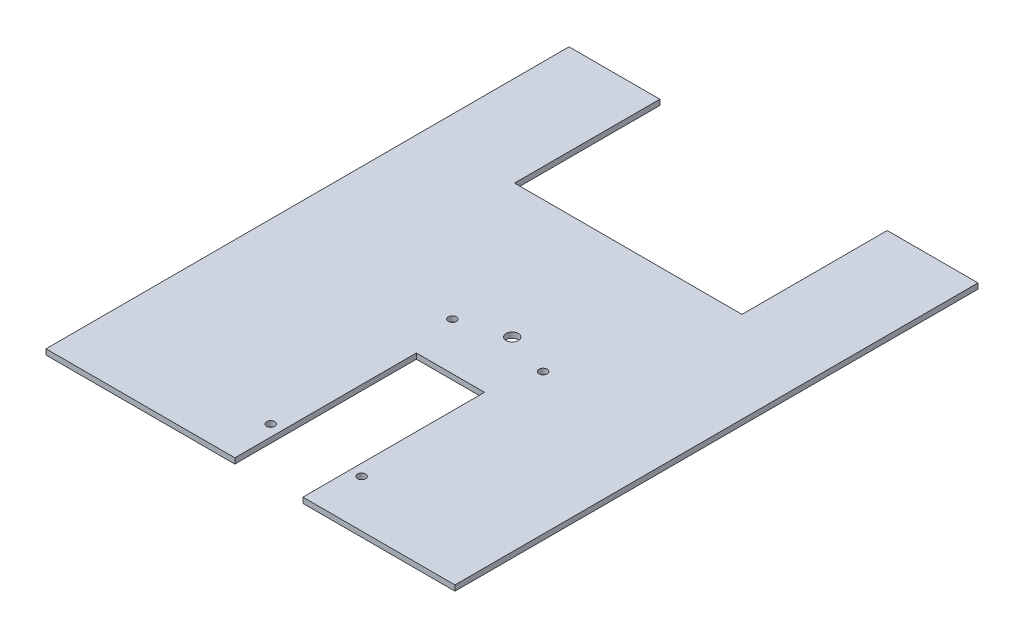
SolidWorks part; units mm, degrees
ref_plane "Front Plane" through (0, 0, 0) normal (0, 0, 1) x (1, 0, 0)
ref_plane "Top Plane" through (0, 0, 0) normal (0, 1, 0) x (1, 0, 0)
ref_plane "Right Plane" through (0, 0, 0) normal (1, 0, 0) x (0, 0, -1)
sketch "Sketch1" plane through (0, 0, 0) normal (0, 1, 0) x (1, 0, 0)
  line L0 (0, 144.035) -> (0, -144.035) construction
  line L1 (-112.62, -144.035) -> (112.62, -144.035)
  line L2 (-112.62, -144.035) -> (-112.62, 144.035)
  line L3 (-112.62, 144.035) -> (112.62, 144.035)
  line L4 (112.62, -144.035) -> (112.62, 144.035)
  dimension "D1" = 288.07
  dimension "D2" = 225.24
extrude "Boss-Extrude1" add sketch "Sketch1" along normal mid plane 3
hole_wizard "M4 Clearance Hole1" positions "Sketch2" profile "Sketch3" hole size "M4" standard "ANSI Metric" end condition up to next
sketch "Sketch2" plane through (0, 1.5, 0) normal (0, 1, 0) x (1, 0, 0)
  point P0 (-14.88, -117.99)
  point P2 (-14.88, -17.99)
  point P4 (35.13, -117.99)
  point P6 (35.13, -17.99)
  point P17 (-14.88, -117.99)
  point P19 (-14.88, -17.99)
  point P21 (35.13, -17.99)
  point P23 (35.13, -117.99)
sketch "Sketch3" plane through (-14.88, 1.5, 117.99) normal (1, 0, 0) x (0, 0, 1)
  line L0 (0, 0) -> (0, 3)
  line L1 (0, 3) -> (2.25, 3)
  line L2 (2.25, 3) -> (2.25, 0)
  line L5 (2.25, 0) -> (0, 0)
  line L11 (0, -6.35) -> (0, 107.95) construction
  dimension "Thru Hole Dia." = 4.5
  dimension "Thru Hole Depth" = 3
hole_wizard "1/4 Clearance Hole1" positions "Sketch4" profile "Sketch5" hole size "1/4" standard "ANSI Inch"
sketch "Sketch4" plane through (0, 1.5, 0) normal (0, 1, 0) x (1, 0, 0)
  line L0 (-112.62, -144.035) -> (112.62, -144.035) construction
  line L1 (-8.63, 8.055) -> (28.88, 8.055) construction
  line L3 (10.125, 8.055) -> (10.125, -10.035) construction
  point P0 (10.125, -10.035)
  dimension "D1" = 134
sketch "Sketch5" plane through (10.125, 1.5, 10.035) normal (1, 0, 0) x (0, 0, 1)
  line L0 (0, 0) -> (0, 22.0298)
  line L1 (0, 22.0298) -> (3.3782, 20)
  line L2 (3.3782, 20) -> (3.3782, 0)
  line L5 (3.3782, 0) -> (0, 0)
  line L10 (0, 22.0298) -> (-3.3782, 20) construction
  line L11 (0, -6.35) -> (0, 107.95) construction
  dimension "Hole Dia." = 6.7564
  dimension "Hole Depth" = 20
  dimension "Drill Angle" = 118
sketch "Sketch6" plane through (0, 1.5, 0) normal (0, 1, 0) x (1, 0, 0)
  line L0 (112.62, 144.035) -> (-112.62, 144.035) construction
  line L1 (62.62, 144.035) -> (-62.62, 144.035)
  line L2 (62.62, 144.035) -> (62.62, 64.035)
  line L3 (62.62, 64.035) -> (-62.62, 64.035)
  line L4 (-62.62, 144.035) -> (-62.62, 64.035)
  line L5 (112.62, -144.035) -> (112.62, 144.035) construction
  line L6 (-112.62, 144.035) -> (-112.62, -144.035) construction
  line L7 (-112.62, -144.035) -> (112.62, -144.035) construction
  line L8 (28.88, -144.035) -> (-8.63, -144.035)
  line L9 (28.88, -144.035) -> (28.88, -44.035)
  line L10 (28.88, -44.035) -> (-8.63, -44.035)
  line L11 (-8.63, -144.035) -> (-8.63, -44.035)
  dimension "D1" = 50
  dimension "D2" = 50
  dimension "D3" = 80
  dimension "D4" = 100
  dimension "D5" = 83.74
  dimension "D6" = 103.99
extrude "Cut-Extrude1" cut sketch "Sketch6" against normal through all
